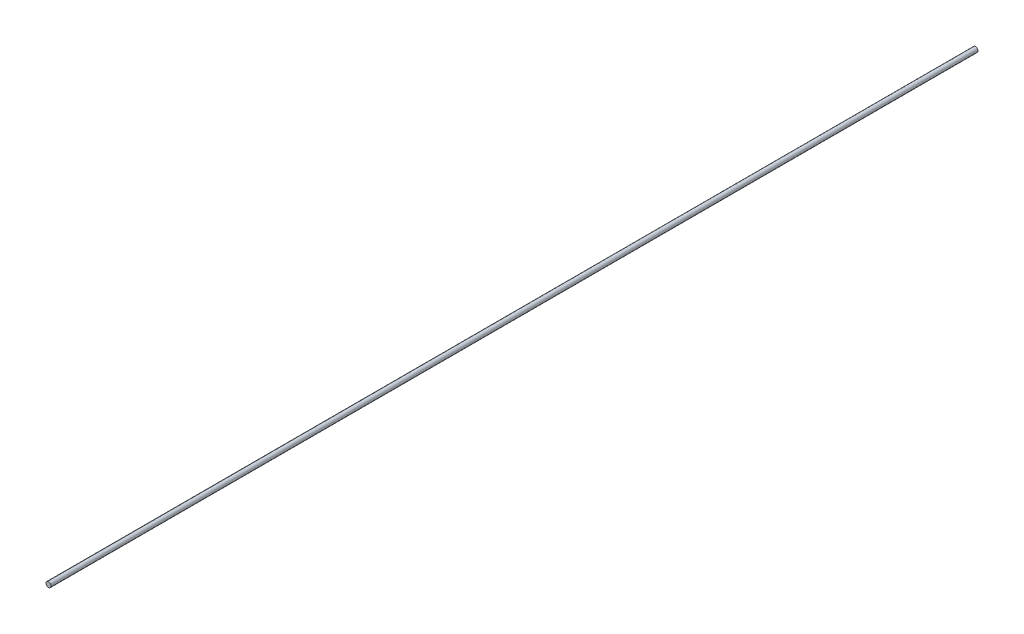
SolidWorks part; units mm, degrees
material "1060 Alloy"
ref_plane "Front Plane" through (0, 0, 0) normal (0, 0, 1) x (1, 0, 0)
ref_plane "Top Plane" through (0, 0, 0) normal (0, 1, 0) x (1, 0, 0)
ref_plane "Right Plane" through (0, 0, 0) normal (1, 0, 0) x (0, 0, -1)
sketch "Sketch1" plane through (0, 0, 0) normal (0, 0, 1) x (1, 0, 0)
  circle A0 centre (0, 0) radius 5.715
  dimension "D1" = 11.43
extrude "Boss-Extrude1" add sketch "Sketch1" along normal blind 2124.71
